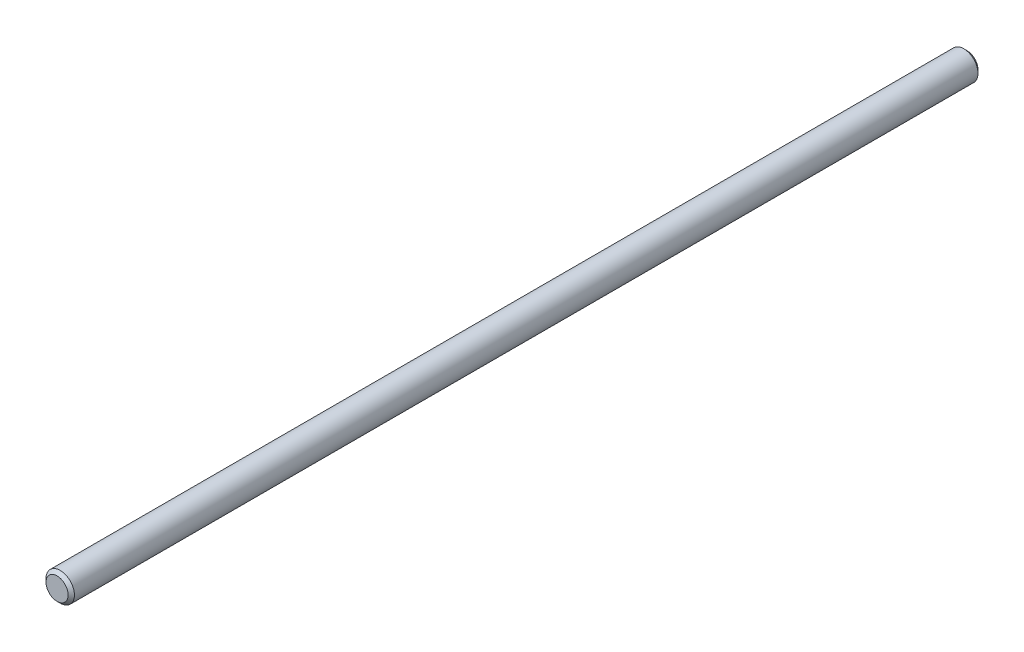
SolidWorks part; units mm, degrees
ref_plane "Front Plane" through (0, 0, 0) normal (0, 0, 1) x (1, 0, 0)
ref_plane "Top Plane" through (0, 0, 0) normal (0, 1, 0) x (1, 0, 0)
ref_plane "Right Plane" through (0, 0, 0) normal (1, 0, 0) x (0, 0, -1)
sketch "Sketch1" plane through (0, 0, 0) normal (1, 0, 0) x (0, 0, -1)
  line L0 (-152.4, 0) -> (152.4, 0) construction
  line L1 (-152.4, 4.7625) -> (-152.4, -4.7625) construction
  line L2 (152.4, 4.7625) -> (152.4, -4.7625) construction
  line L3 (152.3339, 4.8771) -> (153.3922, 4.8771) construction
  line L4 (153.3922, 4.8771) -> (152.863, 3.9605) construction
  line L5 (152.863, 3.9605) -> (152.863, 4.0751) construction
  line L6 (152.3339, 4.8771) -> (152.863, 3.9605) construction
  line L7 (152.4, 4.7625) -> (153.326, 4.7625) construction
  line L8 (152.7969, 4.0751) -> (152.9292, 4.0751) construction
  line L9 (152.863, 4.7625) -> (152.863, 4.8771) construction
  line L10 (152.3669, 4.8198) -> (153.3591, 4.8198) construction
  line L11 (0, 0) -> (0, 4.7625) construction
  line L12 (152.4, -4.7625) -> (129.0637, -4.7625) construction
  point P4 (0, 0)
  point P8 (-152.4, 0)
  point P10 (-101.6, 0)
  point P11 (152.4, 0)
  point P17 (152.863, 4.7625)
  point P20 (152.863, 4.0751)
  point P22 (101.6, 0)
  point P25 (152.863, 4.8198)
  dimension "D1" = 60
  dimension "D2" = 0.1323
  dimension "D3" = 23.3363
sketch "Sketch2" plane through (0, 0, 0) normal (1, 0, 0) x (0, 0, -1)
  line L0 (-152.4, 0) -> (152.4, 0)
  line L1 (152.4, 0) -> (152.4, 3.7042)
  line L2 (151.3417, 4.7625) -> (-151.3417, 4.7625)
  line L3 (-152.4, 3.7042) -> (-152.4, 0)
  line L4 (152.4, 3.7042) -> (151.3417, 4.7625)
  line L5 (-151.3417, 4.7625) -> (-152.4, 3.7042)
  point P5 (152.4, 4.7625)
  point P7 (-152.4, 4.7625)
  dimension "D1" = 1.0583
  dimension "D2" = 45
  dimension "D3" = 1.0583
  dimension "D4" = 45
revolve "Revolve1" add sketch "Sketch2" angle 360 about L0
sketch "Sketch3" plane through (0, 0, -152.4) normal (0, 0, -1) x (-1, 0, 0)
  circle A0 centre (0, 0) radius 4.7625
sketch "Sketch6" plane through (0, 0, 152.4) normal (0, 0, 1) x (1, 0, 0)
  circle A1 centre (0, 0) radius 4.7625
  circle A2 centre (0, 0) radius 4.7625
  dimension "D1" = 0
equation "\"D2@Sketch1\"=\"Pitch@Sketch1\"/8"
equation "\"D1@Sketch2\"=\"Pitch@Sketch1\""
equation "\"D3@Sketch2\"=\"Pitch@Sketch1\""
equation "\"D3@Sketch1\"=(\"Pitch@Sketch1\"+\"Thread Length@Sketch1\") * 0.45"
